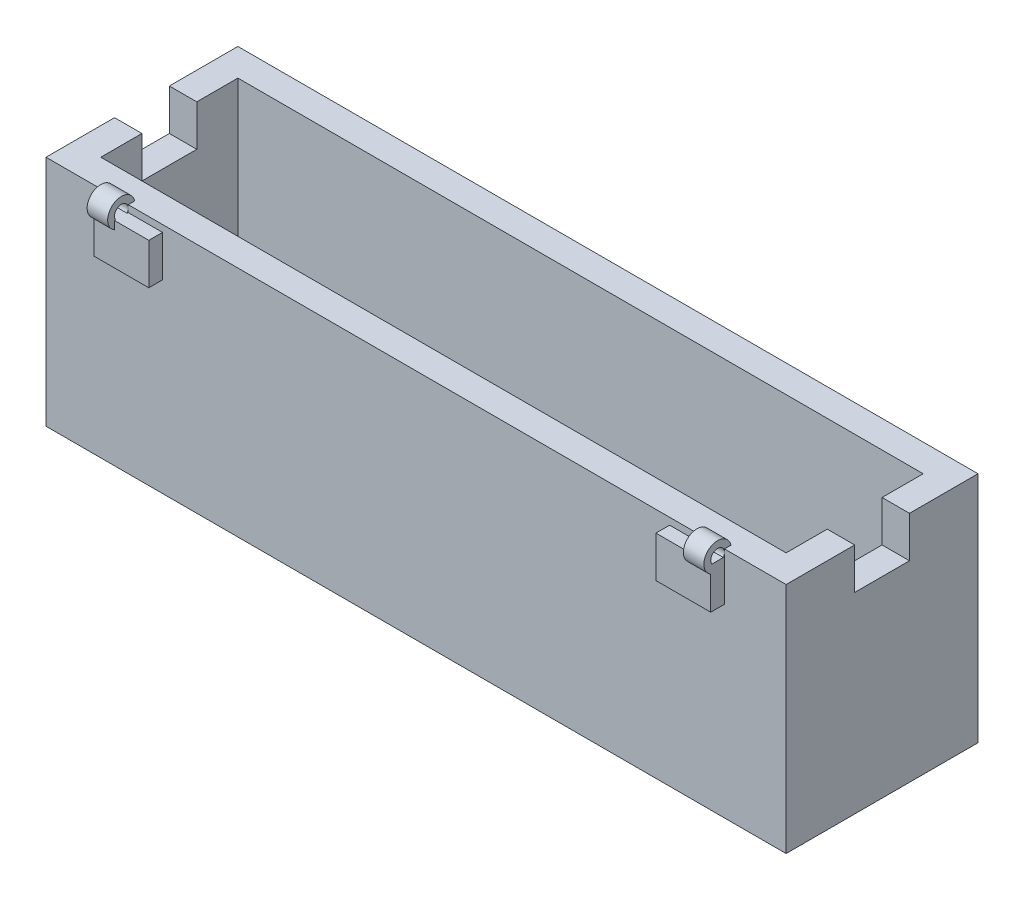
SolidWorks part; units mm, degrees
ref_plane "前基準面" through (0, 0, 0) normal (0, 0, 1) x (1, 0, 0)
ref_plane "上基準面" through (0, 0, 0) normal (0, 1, 0) x (1, 0, 0)
ref_plane "右基準面" through (0, 0, 0) normal (1, 0, 0) x (0, 0, -1)
sketch "草圖1" plane through (0, 0, 0) normal (0, 1, 0) x (1, 0, 0)
  line L1 (-270, 70) -> (270, 70)
  line L2 (-270, 70) -> (-270, -70)
  line L3 (-270, -70) -> (270, -70)
  line L4 (270, 70) -> (270, -70)
  line L5 (-270, 70) -> (270, -70) construction
  line L6 (-270, -70) -> (270, 70) construction
  point P0 (0, 0)
  dimension "D1" = 540
  dimension "D2" = 140
extrude "填料-伸長1" add sketch "草圖1" along normal blind 140
sketch "草圖2" plane through (0, 140, 0) normal (0, 1, 0) x (1, 0, 0)
  line L0 (270, 70) -> (-270, 70) construction
  line L1 (-250, 50) -> (250, 50)
  line L2 (-250, 50) -> (-250, -50)
  line L3 (-250, -50) -> (250, -50)
  line L4 (250, 50) -> (250, -50)
  line L5 (-250, 50) -> (250, -50) construction
  line L6 (-250, -50) -> (250, 50) construction
  line L7 (-270, 70) -> (-270, -70) construction
  point P0 (0, 0)
  dimension "D1" = 20
  dimension "D2" = 20
extrude "除料-伸長1" cut sketch "草圖2" against normal blind 150
ref_plane "平面1" through (0, 0, 80) normal (0, 0, 1) x (1, 0, 0)
sketch "草圖4" plane through (0, 0, 80) normal (0, 0, 1) x (1, 0, 0)
  line L0 (-270, 140) -> (-270, 0) construction
  line L1 (-225, 135) -> (-185, 135)
  line L2 (-225, 135) -> (-225, 105)
  line L3 (-225, 105) -> (-185, 105)
  line L4 (-185, 135) -> (-185, 105)
  line L5 (-225, 135) -> (-185, 105) construction
  line L6 (-225, 105) -> (-185, 135) construction
  line L7 (-270, 140) -> (270, 140) construction
  point P0 (-205, 120)
  dimension "D1" = 45
  dimension "D2" = 5
  dimension "D3" = 30
  dimension "D4" = 40
extrude "填料-伸長2" add sketch "草圖4" against normal blind 30
sketch "草圖5" plane through (0, 0, 80) normal (0, 0, 1) x (1, 0, 0)
  line L0 (-270, 140) -> (270, 140) construction
  line L1 (185, 135) -> (225, 135)
  line L2 (185, 135) -> (185, 105)
  line L3 (185, 105) -> (225, 105)
  line L4 (225, 135) -> (225, 105)
  line L5 (185, 135) -> (225, 105) construction
  line L6 (185, 105) -> (225, 135) construction
  line L7 (270, 140) -> (270, 0) construction
  point P0 (205, 120)
  dimension "D1" = 5
  dimension "D2" = 45
  dimension "D3" = 40
  dimension "D4" = 30
extrude "填料-伸長3" add sketch "草圖5" against normal blind 30
sketch "草圖7" plane through (225, 0, 0) normal (1, 0, 0) x (0, 0, -1)
  line L0 (-75, -865) -> (-75, 49135) construction
  line L1 (-70, 135) -> (-80, 135) construction
  line L2 (-1070, 137.7646) -> (48930, 137.7646) construction
  circle A0 centre (-75, 137.7646) radius 5
  point P5 (-75, 135)
  dimension "D1" = 10
extrude "伸長-薄件1" add sketch "草圖7" against normal blind 15 thin
sketch "草圖9" plane through (-225, 0, 0) normal (-1, 0, 0) x (0, 0, 1)
  line L0 (75, -865) -> (75, 49135) construction
  line L1 (70, 135) -> (80, 135) construction
  line L2 (-930, 137.7646) -> (49070, 137.7646) construction
  circle A1 centre (75, 137.7646) radius 5
  point P5 (75, 135)
extrude "伸長-薄件2" add sketch "草圖9" against normal blind 15 thin
sketch "草圖11" plane through (-270, 0, 0) normal (-1, 0, 0) x (0, 0, 1)
  line L0 (-70, 140) -> (70, 140) construction
  line L1 (-20, 140) -> (20, 140)
  line L2 (-20, 140) -> (-20, 110)
  line L3 (-20, 110) -> (20, 110)
  line L4 (20, 140) -> (20, 110)
  line L5 (-70, 140) -> (-70, 0) construction
  dimension "D1" = 40
  dimension "D2" = 30
  dimension "D3" = 50
extrude "除料-伸長3" cut sketch "草圖11" against normal through all
sketch "草圖12" plane through (-270, 0, 0) normal (-1, 0, 0) x (0, 0, 1)
  line L0 (70, 140) -> (70, 0) construction
  line L1 (38, 130.759) -> (53, 130.759)
  line L2 (38, 130.759) -> (38, 105.759)
  line L3 (38, 105.759) -> (53, 105.759)
  line L4 (53, 130.759) -> (53, 105.759)
  dimension "D1" = 25
  dimension "D2" = 15
  dimension "D3" = 17
sketch "草圖13" plane through (0, 0, 0) normal (0, -1, 0) x (1, 0, 0)
  line L1 (-270, -70) -> (270, -70)
  line L2 (-270, -70) -> (-270, 70)
  line L3 (-270, 70) -> (270, 70)
  line L4 (270, -70) -> (270, 70)
extrude "填料-伸長6" add sketch "草圖13" along normal blind 30
